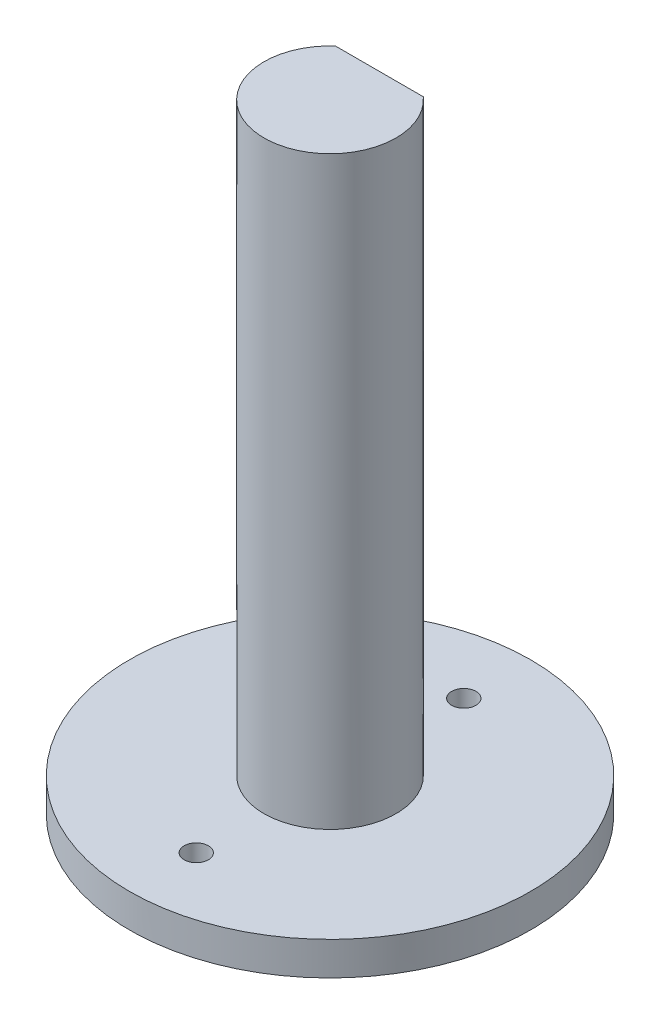
SolidWorks part; units mm, degrees
ref_plane "Alzado" through (0, 0, 0) normal (0, 0, 1) x (1, 0, 0)
ref_plane "Planta" through (0, 0, 0) normal (0, 1, 0) x (1, 0, 0)
ref_plane "Vista lateral" through (0, 0, 0) normal (1, 0, 0) x (0, 0, -1)
sketch "Croquis3" plane through (0, 0, 0) normal (0, 1, 0) x (1, 0, 0)
  circle A0 centre (0, 0) radius 12
  dimension "D1" = 24
extrude "Saliente-Extruir1" add sketch "Croquis3" along normal blind 4
sketch "Croquis4" plane through (0, 4, 0) normal (0, 1, 0) x (1, 0, 0)
  circle A0 centre (0, 0) radius 3.95
  dimension "D1" = 7.9
extrude "Saliente-Extruir2" add sketch "Croquis4" along normal blind 35
sketch "Croquis5" plane through (0, 39, 0) normal (0, 1, 0) x (1, 0, 0)
  line L0 (0, 3.95) -> (0, 2.95) construction
  line L1 (2.6268, 2.95) -> (-2.6268, 2.95)
  circle A0 centre (0, 0) radius 3.95 construction
  arc A1 (2.6268, 2.95) -> (-2.6268, 2.95) centre (0, 0) ccw
  dimension "D1" = 1
extrude "Cortar-Extruir1" cut sketch "Croquis5" against normal blind 20
sketch "Croquis7" plane through (0, 0, 0) normal (0, -1, 0) x (1, 0, 0)
  circle A0 centre (0, 0) radius 12
  dimension "D1" = 24
extrude "Cortar-Extruir2" cut sketch "Croquis7" against normal blind 2 contours A0
sketch "Croquis8" plane through (0, 2, 0) normal (0, -1, 0) x (1, 0, 0)
  line L0 (0, -10.2812) -> (0, 10.4112) construction
  line L1 (-3.151, 0) -> (6.4319, 0) construction
  circle A1 centre (0, 8) radius 0.7264
  circle A2 centre (0, -8) radius 0.7264
  dimension "D1" = 8
extrude "Cortar-Extruir3" cut sketch "Croquis8" against normal through all both and the other way through all
